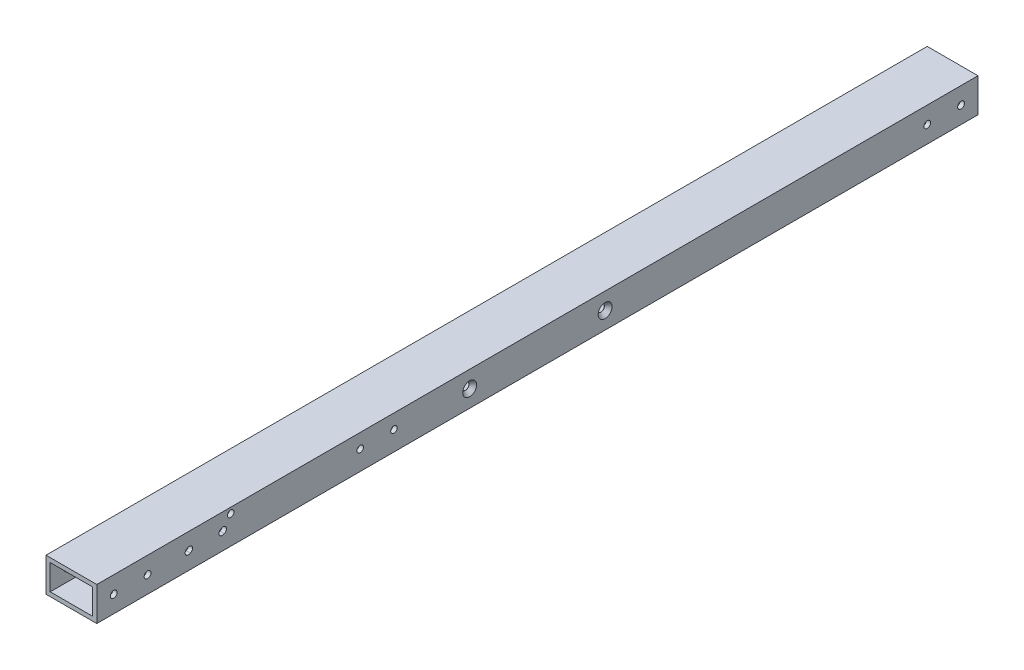
SolidWorks part; units mm, degrees
ref_plane "Front Plane" through (0, 0, 0) normal (0, 0, 1) x (1, 0, 0)
ref_plane "Top Plane" through (0, 0, 0) normal (0, 1, 0) x (1, 0, 0)
ref_plane "Right Plane" through (0, 0, 0) normal (1, 0, 0) x (0, 0, -1)
sketch "Sketch1" plane through (0, 0, 0) normal (0, 0, 1) x (1, 0, 0)
  line L0 (-15.875, 9.525) -> (15.875, 9.525)
  line L2 (-19.05, 12.7) -> (19.05, 12.7)
  line L3 (-19.05, 12.7) -> (-19.05, -12.7)
  line L4 (-19.05, -12.7) -> (19.05, -12.7)
  line L5 (19.05, 12.7) -> (19.05, -12.7)
  line L10 (15.875, 9.525) -> (15.875, -9.525)
  line L11 (-15.875, -9.525) -> (15.875, -9.525)
  line L12 (-15.875, 9.525) -> (-15.875, -9.525)
  point P12 (0, 12.7)
  point P14 (19.05, 0)
  dimension "Wall Thickness" = 3.175
  dimension "Outside Width" = 38.1
  dimension "Outside Height" = 25.4
  dimension "Inside Height" = 19.05
  dimension "Inside Width" = 31.75
sketch "Sketch2" plane through (0, 0, 0) normal (1, 0, 0) x (0, 0, -1)
  line L0 (330.5556, 0) -> (-330.5556, 0)
  point P4 (0, 0)
  point P7 (-330.5556, 0)
  point P10 (330.5556, 0)
  dimension "Length" = 661.1112
sketch "Sketch3" plane through (0, 0, 0) normal (0, 0, 1) x (1, 0, 0)
  line L21 (19.05, 12.7) -> (-19.05, 12.7)
  line L22 (19.05, -12.7) -> (19.05, 12.7)
  line L23 (-19.05, -12.7) -> (19.05, -12.7)
  line L24 (-19.05, 12.7) -> (-19.05, -12.7)
  line L25 (19.05, 12.7) -> (-19.05, 12.7)
  line L26 (19.05, -12.7) -> (19.05, 12.7)
  line L27 (-19.05, -12.7) -> (19.05, -12.7)
  line L28 (-19.05, 12.7) -> (-19.05, -12.7)
  line L29 (15.875, 9.525) -> (-15.875, 9.525)
  line L30 (15.875, -9.525) -> (15.875, 9.525)
  line L31 (-15.875, -9.525) -> (15.875, -9.525)
  line L32 (-15.875, 9.525) -> (-15.875, -9.525)
  line L33 (15.875, 9.525) -> (-15.875, 9.525)
  line L34 (15.875, -9.525) -> (15.875, 9.525)
  line L35 (-15.875, -9.525) -> (15.875, -9.525)
  line L36 (-15.875, 9.525) -> (-15.875, -9.525)
  dimension "D1" = 0
  dimension "D2" = 0
extrude "Boss-Extrude1" add sketch "Sketch3" along normal up to vertex (330.5556 mm away) and the other way up to vertex (330.5556 mm away) up to point (0, 0, 330.5556) other way up to point (0, 0, -330.5556)
sketch "Drawing Reference" plane through (0, 0, 0) normal (1, 0, 0) x (0, 0, -1)
  line L0 (-330.5556, 0) -> (330.5556, 0) construction
  line L1 (0, -12.7) -> (0, 12.7) construction
  line L2 (-330.5556, -12.7) -> (330.5556, -12.7) construction
  line L5 (-330.5556, 12.7) -> (330.5556, 12.7) construction
  point P7 (-303.1236, 0)
  point P8 (303.1236, 0)
  dimension "D1" = 27.432
sketch "Sketch4" plane through (-19.05, 0, 0) normal (-1, 0, 0) x (0, 0, 1)
  line L0 (-330.5556, 0) -> (-317.8556, 0)
  line L1 (-330.5556, 12.7) -> (-330.5556, -12.7) construction
  line L2 (-317.8556, 0) -> (-292.4556, 0)
  line L3 (330.5556, 12.7) -> (330.5556, -12.7) construction
  line L4 (330.5556, 0) -> (317.8556, 0)
  line L5 (317.8556, 0) -> (292.4556, 0)
  line L6 (0, 0) -> (50.8, 0) construction
  line L7 (0, 0) -> (-50.8, 0) construction
  point P11 (-317.8556, 0)
  point P13 (-292.4556, 0)
  point P14 (317.8556, 0)
  point P15 (292.4556, 0)
hole_wizard "#10 Clearance Hole2" positions "Sketch11" profile "Sketch12" hole size "#10" standard "ANSI Inch" end condition through all
sketch "Sketch11" plane through (-19.05, 0, 0) normal (-1, 0, 0) x (0, 0, 1)
  point P0 (-317.8556, 0)
  point P3 (-292.4556, 0)
  point P6 (292.4556, 0)
  point P9 (317.8556, 0)
sketch "Sketch12" plane through (-19.05, 0, -317.8556) normal (0, 1, 0) x (0, 0, 1)
  line L0 (0, 0) -> (0, 38.1)
  line L1 (0, 38.1) -> (2.5527, 38.1)
  line L2 (2.5527, 38.1) -> (2.5527, 0)
  line L5 (2.5527, 0) -> (0, 0)
  line L11 (0, -6.35) -> (0, 107.95) construction
  dimension "Thru Hole Dia." = 5.1054
  dimension "Thru Hole Depth" = 38.1
hole_wizard "#10 (0.1935) Diameter Hole1" positions "Sketch14" profile "Sketch16" hole size "#10" standard "ANSI Inch" end condition through all
sketch "Sketch14" plane through (19.05, 0, 0) normal (1, 0, 0) x (0, 0, -1)
  point P33 (-261.1289, 0.3559)
  point P36 (-235.7289, 0.3559)
  point P39 (-230.0465, 8.4736)
  point P42 (-132.9849, 1.9434)
  point P45 (-107.5849, 1.9434)
sketch "Sketch16" plane through (19.05, 0.3559, 261.1289) normal (0, 1, 0) x (0, 0, -1)
  line L0 (0, 0) -> (0, 38.1)
  line L1 (0, 38.1) -> (2.4574, 38.1)
  line L2 (2.4574, 38.1) -> (2.4574, 0)
  line L5 (2.4574, 0) -> (0, 0)
  line L11 (0, -6.35) -> (0, 107.95) construction
  dimension "Thru Hole Dia." = 4.9149
  dimension "Thru Hole Depth" = 38.1
sketch "Sketch17" plane through (19.05, 0, 0) normal (1, 0, 0) x (0, 0, -1)
  point P0 (-261.8407, 0)
  point P1 (-236.4407, 0)
hole_wizard "#10 (0.1935) Diameter Hole2" positions "Sketch18" profile "Sketch19" hole size "#10" standard "ANSI Inch" end condition through all
sketch "Sketch18" plane through (19.05, 0, 0) normal (1, 0, 0) x (0, 0, -1)
  point P0 (-261.8407, 0)
  point P3 (-236.4407, 0)
sketch "Sketch19" plane through (19.05, 0, 261.8407) normal (0, 1, 0) x (0, 0, -1)
  line L0 (0, 0) -> (0, 38.1)
  line L1 (0, 38.1) -> (2.4574, 38.1)
  line L2 (2.4574, 38.1) -> (2.4574, 0)
  line L5 (2.4574, 0) -> (0, 0)
  line L11 (0, -6.35) -> (0, 107.95) construction
  dimension "Thru Hole Dia." = 4.9149
  dimension "Thru Hole Depth" = 38.1
hole_wizard "#10 Clearance Hole3" positions "Sketch20" profile "Sketch21" hole size "#10" standard "ANSI Inch" end condition through all
sketch "Sketch20" plane through (-19.05, 0, 0) normal (-1, 0, 0) x (0, 0, 1)
  point P0 (-50.8, 0)
  point P3 (50.8, 0)
sketch "Sketch21" plane through (-19.05, 0, -50.8) normal (0, 1, 0) x (0, 0, 1)
  line L0 (0, 0) -> (0, 38.1)
  line L1 (0, 38.1) -> (5.207, 38.1)
  line L2 (2.5527, 35.0466) -> (2.5527, 0)
  line L5 (2.5527, 0) -> (0, 0)
  line L7 (5.207, 38.1) -> (2.5527, 35.0466)
  line L8 (-5.207, 38.1) -> (-2.5527, 35.0466) construction
  line L11 (0, -6.35) -> (0, 107.95) construction
  dimension "Thru Hole Dia." = 5.1054
  dimension "Thru Hole Depth" = 38.1
  dimension "Far C'Sink Dia." = 10.414
  dimension "Far C'Sink Angle" = 82
equation "\"D1@Drawing Reference\"=\"Outside Width@Sketch1\" * 0.72"
